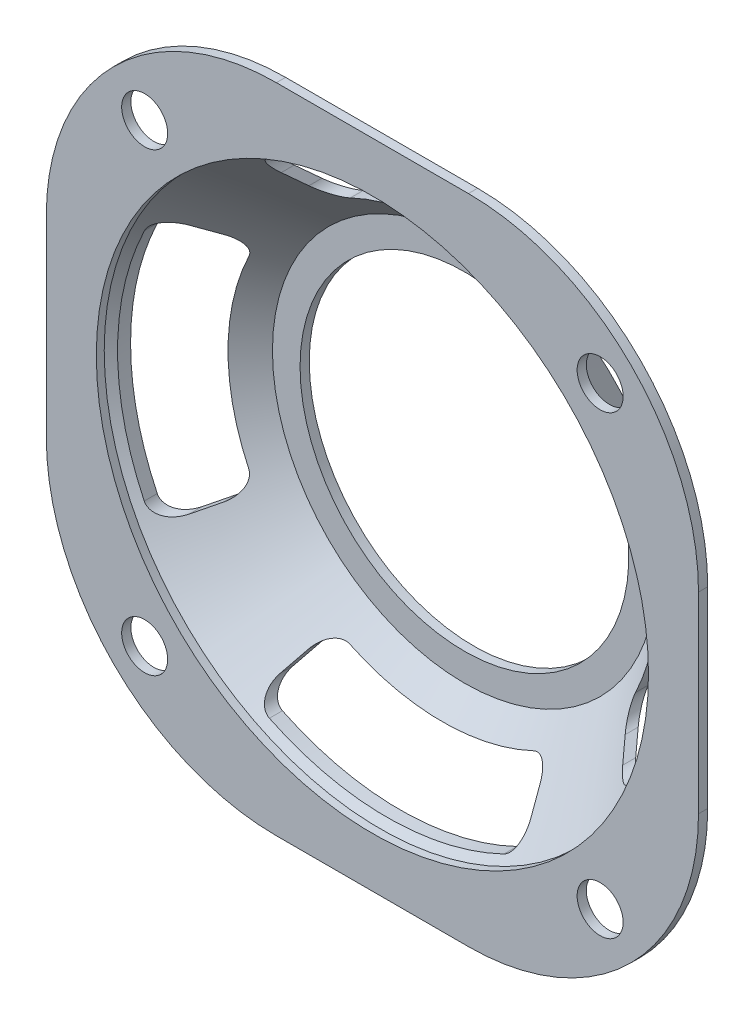
SolidWorks part; units mm, degrees
ref_plane "前基準面" through (0, 0, 0) normal (0, 0, 1) x (1, 0, 0)
ref_plane "上基準面" through (0, 0, 0) normal (0, 1, 0) x (1, 0, 0)
ref_plane "右基準面" through (0, 0, 0) normal (1, 0, 0) x (0, 0, -1)
sketch "草圖1" plane through (0, 0, 0) normal (0, 0, 1) x (1, 0, 0)
  line L0 (-24.745, 24.745) -> (24.745, -24.745) construction
  line L1 (-24.745, 24.745) -> (24.745, 24.745) construction
  line L2 (-24.745, 24.745) -> (-24.745, -24.745) construction
  line L3 (-24.745, -24.745) -> (24.745, -24.745) construction
  line L4 (24.745, 24.745) -> (24.745, -24.745) construction
  line L5 (-24.745, -24.745) -> (24.745, 24.745) construction
  line L6 (24.745, -24.745) -> (36.1515, -36.1515) construction
  line L7 (-24.745, -24.745) -> (-37.8238, -36.1515) construction
  line L8 (0, 0) -> (0, -48.7076) construction
  line L9 (0, 0) -> (14.2088, 0) construction
  line L10 (-35.4336, -10.4336) -> (-35.4336, 10.4336)
  line L11 (35.4336, -10.4336) -> (35.4336, 10.4336)
  line L12 (10.4336, -35.4336) -> (-10.4336, -35.4336)
  line L13 (-24.745, 24.745) -> (-37.8238, 40.0815) construction
  line L14 (-10.4336, 35.4336) -> (10.4336, 35.4336)
  circle A0 centre (-24.745, 24.745) radius 2.5
  circle A1 centre (24.745, 24.745) radius 2.5
  circle A2 centre (24.745, -24.745) radius 2.5
  circle A3 centre (-24.745, -24.745) radius 2.5
  circle A4 centre (0, 0) radius 30
  arc A5 (-10.4336, 35.4336) -> (-35.4336, 10.4336) centre (-10.4336, 10.4336) ccw
  arc A6 (10.4336, 35.4336) -> (35.4336, 10.4336) centre (10.4336, 10.4336) cw
  arc A7 (10.4336, -35.4336) -> (35.4336, -10.4336) centre (10.4336, -10.4336) ccw
  arc A8 (-10.4336, -35.4336) -> (-35.4336, -10.4336) centre (-10.4336, -10.4336) cw
  dimension "D1" = 5
  dimension "D2" = 60
  dimension "D5" = 50
  dimension "D3" = 49.49
  dimension "D4" = 49.49
extrude "填料-伸長1" add sketch "草圖1" along normal blind 1
sketch "草圖2" plane through (0, 0, 0) normal (1, 0, 0) x (0, 0, -1)
  line L0 (9, 20.8602) -> (-1, 30.8602)
  line L1 (24.5781, 0) -> (0, 0) construction
  line L2 (9, 20.8602) -> (9, 17.8602)
  line L3 (-1, 35.4336) -> (-1, 10.4336) construction
  line L4 (-1, 30.8602) -> (-1, 31.8602)
  dimension "D1" = 10
  dimension "D2" = 1
  dimension "D3" = 135
  dimension "D4" = 3
revolve "旋轉-薄件1" add sketch "草圖2" angle 360 about L1
sketch "草圖3" plane through (0, 0, 0) normal (0, 0, 1) x (1, 0, 0)
  line L0 (0, 0) -> (-42.5655, -24.4937) construction
  line L1 (0, 0) -> (-42.2131, 24.4527) construction
  line L2 (-23.5372, 13.6344) -> (-21.8016, 12.6289)
  line L3 (-21.8378, -12.5662) -> (-23.5763, -13.5666)
  arc A0 (-26.3392, 12.7766) -> (-26.3758, -12.7009) centre (0, 0) ccw
  arc A1 (-20.9995, 10.0359) -> (-21.0283, -9.9755) centre (0, 0) ccw
  circle A2 centre (0, 0) radius 21.2745 construction
  circle A3 centre (0, 0) radius 31.2745 construction
  arc A4 (-23.5763, -13.5666) -> (-26.3758, -12.7009) centre (-24.5738, -11.8332) cw
  arc A5 (-21.8378, -12.5662) -> (-21.0283, -9.9755) centre (-22.8353, -10.8327) ccw
  arc A6 (-21.8016, 12.6289) -> (-20.9995, 10.0359) centre (-22.804, 10.8983) cw
  arc A7 (-23.5372, 13.6344) -> (-26.3392, 12.7766) centre (-24.5397, 11.9037) ccw
  point P14 (-25.3734, -14.6008)
  point P17 (-20.173, -11.6082)
  point P20 (-20.1395, 11.6662)
  point P23 (-25.3314, 14.6737)
  dimension "D2" = 2
  dimension "D3" = 2
  dimension "D4" = 2
  dimension "D1" = 60
extrude "除料-伸長1" cut sketch "草圖3" against normal through all
pattern_circular "環狀複製排列1" count 4 over 360 about axis through (0, 0, 0) along (0, 0, 1) of "除料-伸長1"
